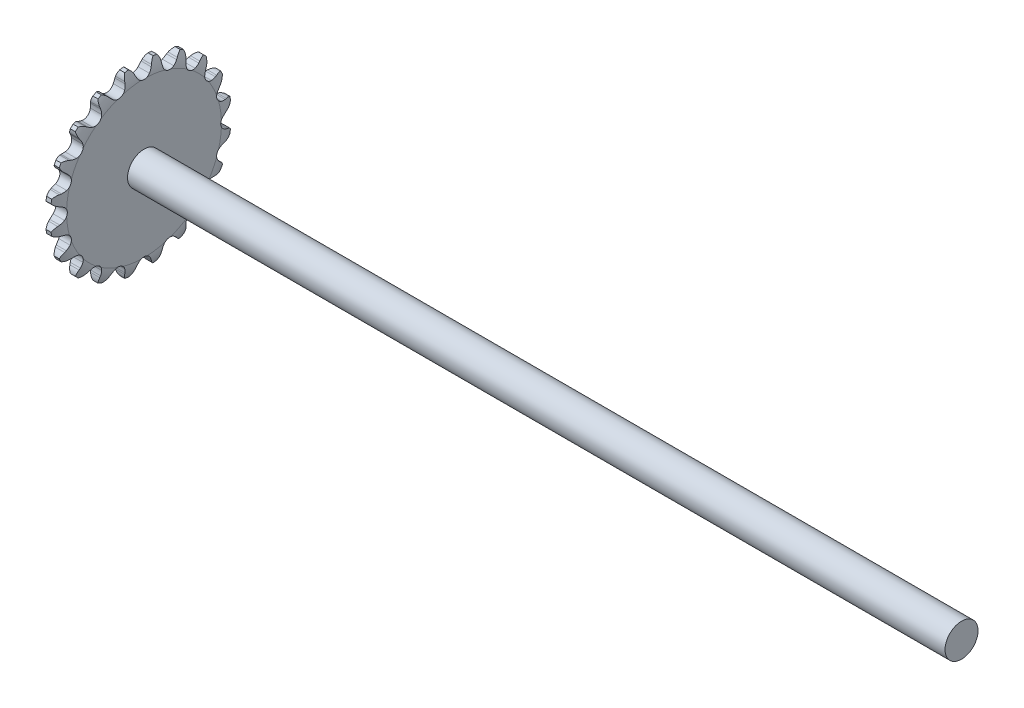
SolidWorks part; units mm, degrees
ref_plane "Plane1" through (0, 0, 0) normal (0, 0, 1) x (1, 0, 0)
ref_plane "Plane2" through (0, 0, 0) normal (0, 1, 0) x (1, 0, 0)
ref_plane "Plane3" through (0, 0, 0) normal (1, 0, 0) x (0, 0, -1)
other "Configuration Table"
sketch "Clipboard" plane through (0, 0, 0) normal (0, 1, 0) x (1, 0, 0)
  line L0 (0, 0) -> (5.967, -2.1718)
  line L1 (-15, 0) -> (100, 0) construction
  line L2 (0, 0) -> (-0.5218, 0.5897)
  line L3 (0, 0) -> (-2.9658, 1.1335)
  line L4 (0, 0) -> (2.9835, 1.0859)
  line L5 (0, 0) -> (-47.5972, -17.7524)
  line L6 (0, 0) -> (-2.3214, -1.5662)
  line L7 (-0.5218, 0.5897) -> (46.9042, 18.7948)
  line L8 (-76.2, 38.1) -> (-67.9958, 38.1)
  line L9 (-73.2057, 38.5609) -> (-73.0533, 38.5634)
  line L10 (-73.0533, 76.1892) -> (-66.6525, 76.1892)
  circle A0 centre (0, 0) radius 1.651
  circle A1 centre (0, 0) radius 16.4902
  circle A2 centre (0, 0) radius 38.1
  dimension "Dr" = 3.302
  dimension "MHD" = 32.9803
  dimension "Hub_dia" = 76.2
  dimension "Num_teeth" = 20
  dimension "Pitch" = 6.35
  dimension "Width" = 3.175
  dimension "Chamfer_wid" = 0.7874
  dimension "Chamfer_dep" = 3.175
  dimension "Overall_len" = 50.8
  dimension "Show_teeth" = 20
  dimension "Thickness" = 2.8003
  dimension "OAL" = 50.8001
  dimension "T_dim" = 8.2042
  dimension "Width_const" = 0.1524
  dimension "Width_factor" = 0.93
  dimension "Num_strands" = 1
  dimension "Transv_pitch" = 6.4008
sketch "BasProSke" plane through (0, 0, 0) normal (0, 1, 0) x (1, 0, 0)
  line L0 (-10, 0) -> (60, 0) construction
  line L1 (0, 0) -> (0, 18.7762)
  line L2 (0, 0) -> (2.8003, 0)
  line L3 (2.8003, 0) -> (2.8003, 18.7762)
  line L4 (2.0129, 21.9512) -> (0.7874, 21.9512)
  arc A0 (0, 18.7762) -> (0.7874, 21.9512) centre (6.7949, 18.7762) cw
  arc A1 (2.8003, 18.7762) -> (2.0129, 21.9512) centre (-3.9946, 18.7762) ccw
  dimension "Thickness" = 2.8003
  dimension "D1" = 6.7949
  dimension "G1" = 0.7874
  dimension "G2" = 0.7874
  dimension "H2" = 3.175
  dimension "H1" = 3.175
  dimension "Diameter" = 43.9023
revolve "Base-Revolve" add sketch "BasProSke" angle 360 about L0
sketch "GrvSke" plane through (0, 0, 0) normal (0, 1, 0) x (1, 0, 0)
  line L0 (2.8003, 18.7762) -> (2.8003, 16.4902)
  line L1 (2.8003, 16.4902) -> (6.4008, 16.4902)
  line L2 (6.4008, 16.4902) -> (6.4008, 18.7762)
  line L3 (2.0129, 21.9512) -> (7.1882, 21.9512)
  line L4 (4.6006, 0) -> (4.6006, 52.07) construction
  line L5 (-10, 0) -> (60, 0) construction
  line L6 (0, 0) -> (35.56, 0) construction
  arc A0 (6.4008, 18.7762) -> (7.1882, 21.9512) centre (13.1957, 18.7762) cw
  arc A1 (2.8003, 18.7762) -> (2.0129, 21.9512) centre (-3.9946, 18.7762) ccw
  dimension "G1" = 0.7874
  dimension "H1" = 3.175
  dimension "Diameter" = 43.9023
  dimension "Grv_diam" = 32.9803
  dimension "Grv_width" = 3.6004
  dimension "Offset" = 4.6006
revolve "Groove" [suppressed] cut sketch "GrvSke" angle 360 about L6
pattern_linear "Grooves" [suppressed]
sketch "TooCutSke" plane through (0, 0, 0) normal (1, 0, 0) x (0, 0, -1)
  line L0 (1.9183, 20.241) -> (2.0772, 20.619)
  line L1 (0, 0) -> (0, 107) construction
  line L2 (0, 20.296) -> (-10, 20.296) construction
  line L3 (-1.9183, 20.241) -> (-2.0772, 20.619)
  arc A0 (1.3375, 19.251) -> (1.9183, 20.241) centre (-2.0816, 21.9224) ccw
  arc A1 (1.3375, 19.251) -> (-1.3375, 19.251) centre (0, 20.296) cw
  arc A2 (2.0772, 20.619) -> (4.5659, 22.2725) centre (4.5659, 19.5729) cw
  arc A3 (-1.3375, 19.251) -> (-1.9183, 20.241) centre (2.0816, 21.9224) cw
  arc A4 (-2.0772, 20.619) -> (-4.5659, 22.2725) centre (-4.5659, 19.5729) ccw
  arc A5 (4.5659, 22.2725) -> (-4.5659, 22.2725) centre (0, 0) ccw
  dimension "R" = 1.6974
  dimension "E" = 4.339
  dimension "F" = 2.6996
  dimension "Pitch_radius" = 20.296
  dimension "W" = 4.5659
  dimension "V" = 0.7232
  dimension "A" = 38
  dimension "B" = 15.2
extrude "ToothCut" cut sketch "TooCutSke" along normal through all
pattern_circular "TeethCuts" count 20 every 18 about axis through (-10, 0, 0) along (1, 0, 0) of "ToothCut"
sketch "HubNeaOneSke" plane through (0, 0, 0) normal (-1, 0, 0) x (0, 0, 1)
  circle A0 centre (0, 0) radius 16.4902
  dimension "Diameter" = 32.9803
extrude "HubNearOne" [suppressed] add sketch "HubNeaOneSke" along normal blind 47.9997
sketch "HubNeaBotSke" plane through (0, 0, 0) normal (-1, 0, 0) x (0, 0, 1)
  circle A0 centre (0, 0) radius 16.4902
  dimension "Diameter" = 32.9803
extrude "HubNearBoth" [suppressed] add sketch "HubNeaBotSke" along normal blind 23.9999
ref_plane "FarPln" through (2.8003, 0, 0) normal (1, 0, 0) x (0, 0, -1)
sketch "HubFarSke" plane through (2.8003, 0, 0) normal (1, 0, 0) x (0, 0, -1)
  circle A0 centre (0, 0) radius 16.4902
  dimension "Diameter" = 32.9803
extrude "HubFar" [suppressed] add sketch "HubFarSke" along normal blind 23.9999
sketch "BorSke" plane through (0, 0, 0) normal (1, 0, 0) x (0, 0, -1)
  circle A0 centre (0, 0) radius 4
  dimension "Diameter" = 8
extrude "Bore" cut sketch "BorSke" along normal mid plane 101.6001
sketch "KeySke" plane through (0, 0, 0) normal (1, 0, 0) x (0, 0, -1)
  line L0 (-0.127, 0) -> (-0.127, 4.2042)
  line L1 (-0.127, 4.2042) -> (0.127, 4.2042)
  line L2 (0.127, 4.2042) -> (0.127, 0)
  line L3 (0, 0) -> (0, 34) construction
  line L4 (-0.127, 0) -> (0.127, 0)
  dimension "Offset" = 4.2042
  dimension "Width" = 0.254
extrude "Keyway" [suppressed] cut sketch "KeySke" along normal mid plane 101.6001
pattern_circular "Keyway2" [suppressed] count 2 every 90 about axis through (-10, 0, 0) along (1, 0, 0)
sketch "Sketch1" plane through (0, 0, 0) normal (-1, 0, 0) x (0, 0, 1)
  circle A0 centre (0, 0) radius 4 construction
  circle A1 centre (0, 0) radius 4
extrude "Boss-Extrude1" add sketch "Sketch1" against normal blind 201
equation "\"Num_teeth@Clipboard\" = int( \"Num_teeth@Clipboard\" )"
equation "\"Num_teeth@Clipboard\" = ((sgn( \"Num_teeth@Clipboard\" - 5.0)+1)*( \"Num_teeth@Clipboard\" - 5.0))/2 +5.0"
equation "\"Num_teeth@Clipboard\" = ((sgn( \"Num_teeth@Clipboard\" - 200.0)-1)*( \"Num_teeth@Clipboard\" - 200.0))/-2 +200.0"
equation "\"MHD@Clipboard\" = \"Pitch@Clipboard\" * (1.0 / tan(3.14159265 / \"Num_teeth@Clipboard\" ) - 1.0) - 0.03"
equation "\"Thickness@Clipboard\"  = \"Width@Clipboard\" * \"Width_factor@Clipboard\" - \"Width_const@Clipboard\" + (\"Num_strands@Clipboard\" - 1) * \"Transv_pitch@Clipboard\""
equation "\"OAL@Clipboard\" = \"Thickness@Clipboard\""
equation "\"MHD@Clipboard\" = ((sgn( \"MHD@Clipboard\" - \"Hub_dia@Clipboard\" )-1)*( \"MHD@Clipboard\" - \"Hub_dia@Clipboard\" ))/-2+ \"Hub_dia@Clipboard\""
equation "\"OAL@Clipboard\" = ((sgn( \"OAL@Clipboard\" - \"Overall_len@Clipboard\" )+1)*( \"OAL@Clipboard\" - \"Overall_len@Clipboard\" ))/2 + \"Overall_len@Clipboard\" + 0.000002"
equation "\"Num_teeth@TeethCuts\" = int( \"Show_teeth@Clipboard\" ) + 1"
equation "\"Num_teeth@TeethCuts\" = ((sgn( \"Num_teeth@TeethCuts\" - \"Num_teeth@Clipboard\" )-1)*( \"Num_teeth@TeethCuts\" - \"Num_teeth@Clipboard\" ))/-2+ \"Num_teeth@Clipboard\""
equation "\"Num_teeth@TeethCuts\" = ((sgn( \"Num_teeth@TeethCuts\" - 2.0)+1)*( \"Num_teeth@TeethCuts\" - 2.0))/2 +2.0"
equation "\"Angle@TeethCuts\" = 360.0 / \"Num_teeth@Clipboard\""
equation "\"Pitch_radius@TooCutSke\" = ( \"Pitch@Clipboard\" / 2.0) / sin(3.14159265 / \"Num_teeth@Clipboard\" )  'ma"
equation "\"R@TooCutSke\"  = \"Dr@Clipboard\" * 0.5025 + 0.0015"
equation "\"A@TooCutSke\" = 35.0 + (60.0 / \"Num_teeth@Clipboard\")"
equation "\"E@TooCutSke\"  = \"Dr@Clipboard\" * 1.3025 + 0.0015"
equation "\"B@TooCutSke\"  = 18.0 - (56.0 / \"Num_teeth@Clipboard\" )"
equation "\"W@TooCutSke\" = 1.4 * \"Dr@Clipboard\" * cos(3.14159265 / \"Num_teeth@Clipboard\" )"
equation "\"V@TooCutSke\" = 1.4 * \"Dr@Clipboard\" * sin(3.14159265 / \"Num_teeth@Clipboard\" )"
equation "\"Diameter@BasProSke\" = 2.0 * ( (0.3 * \"Pitch@Clipboard\" ) +  \"Pitch@Clipboard\" / 2.0 / tan(3.14159265 / \"Num_teeth@Clipboard\" ))"
equation "\"Thickness@BasProSke\"  = \"Thickness@Clipboard\""
equation "\"G1@BasProSke\" =  \"Chamfer_wid@Clipboard\""
equation "\"G2@BasProSke\" =  \"Chamfer_wid@Clipboard\""
equation "\"H1@BasProSke\" =  \"Chamfer_dep@Clipboard\""
equation "\"H2@BasProSke\" =  \"Chamfer_dep@Clipboard\""
equation "\"Diameter@GrvSke\" = \"Diameter@BasProSke\""
equation "\"G1@GrvSke\" = \"Chamfer_wid@Clipboard\""
equation "\"H1@GrvSke\" = \"Chamfer_dep@Clipboard\""
equation "\"Grv_diam@GrvSke\" =  \"Pitch@Clipboard\" * (1.0 / tan(3.14159265 / \"Num_teeth@Clipboard\" ) - 1.0) - 0.03"
equation "\"Grv_width@GrvSke\" =  \"Transv_pitch@Clipboard\" - ( \"Width@Clipboard\" * \"Width_factor@Clipboard\" - \"Width_const@Clipboard\" )"
equation "\"Offset@GrvSke\" = \"Grv_width@GrvSke\" / 2.0 + ( \"Width@Clipboard\" * \"Width_factor@Clipboard\" - \"Width_const@Clipboard\" )"
equation "\"Offset@Grooves\" = \"Transv_pitch@Clipboard\""
equation "\"Num_grvs@Grooves\" = \"Num_strands@Clipboard\""
equation "\"Num_grvs@Grooves\" = \"Num_grvs@Grooves\" - 1 * sgn( \"Num_grvs@Grooves\" -1)"
equation "\"Diameter@HubNeaOneSke\" = \"MHD@Clipboard\""
equation "\"Length@HubNearOne\" = \"OAL@Clipboard\" - \"Thickness@BasProSke\""
equation "\"Diameter@HubNeaBotSke\" = \"MHD@Clipboard\""
equation "\"Length@HubNearBoth\" = ( \"OAL@Clipboard\" - \"Thickness@BasProSke\" ) / 2.0"
equation "\"Thickness@FarPln\" = \"Thickness@BasProSke\""
equation "\"Diameter@HubFarSke\" = \"MHD@Clipboard\""
equation "\"Length@HubFar\" = ( \"OAL@Clipboard\" - \"Thickness@BasProSke\" ) / 2.0"
equation "\"D1@Bore\" = \"OAL@Clipboard\" * 2.0"
equation "\"D1@Keyway\" = \"OAL@Clipboard\" * 2.0"
equation "\"Offset@KeySke\" = \"T_dim@Clipboard\" - \"Diameter@BorSke\" / 2.0"
